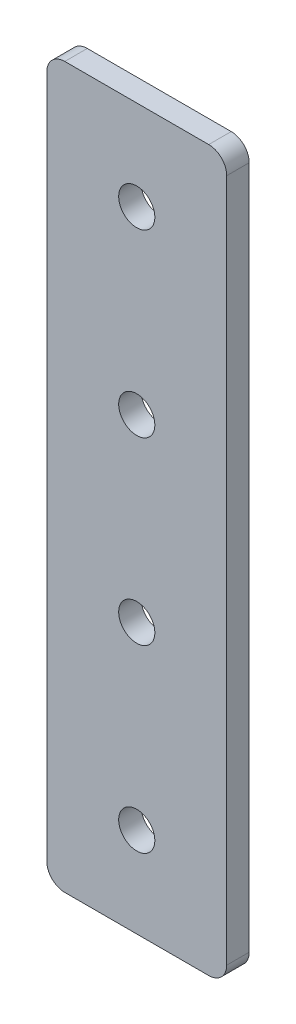
SolidWorks part; units mm, degrees
ref_plane "Front Plane" through (0, 0, 0) normal (0, 0, 1) x (1, 0, 0)
ref_plane "Top Plane" through (0, 0, 0) normal (0, 1, 0) x (1, 0, 0)
ref_plane "Right Plane" through (0, 0, 0) normal (1, 0, 0) x (0, 0, -1)
sketch "Sketch1" plane through (0, 0, 0) normal (0, 0, 1) x (1, 0, 0)
  line L1 (0, 0) -> (-25.4, 0)
  line L2 (0, 0) -> (0, 101.6)
  line L3 (0, 101.6) -> (-25.4, 101.6)
  line L4 (-25.4, 0) -> (-25.4, 101.6)
  line L5 (-12.7, 88.9) -> (-12.7, 63.5) construction
  circle A0 centre (-12.7, 88.9) radius 2.5527
  circle A6 centre (-12.7, 63.5) radius 2.5527
  circle A7 centre (-38.1, 88.9) radius 2.5527 [skipped]
  circle A8 centre (-38.1, 63.5) radius 2.5527 [skipped]
  circle A9 centre (-12.7, 38.1) radius 2.5527
  circle A11 centre (-38.1, 38.1) radius 2.5527 [skipped]
  circle A12 centre (-12.7, 12.7) radius 2.5527
  circle A14 centre (-38.1, 12.7) radius 2.5527 [skipped]
  dimension "D3" = 5.1054
  dimension "D1" = 101.6
  dimension "D2" = 25.4
  dimension "D4" = 12.7
  dimension "D5" = 12.7
  dimension "D9" = 25.4
  dimension "D6" = 2
  dimension "D7" = 4
extrude "Boss-Extrude1" add sketch "Sketch1" along normal blind 3.175
fillet "Fillet1" radius 2.54 4 edges at (0, 0, 1.5875) (-25.4, 0, 1.5875) (0, 101.6, 1.5875) (-25.4, 101.6, 1.5875)
